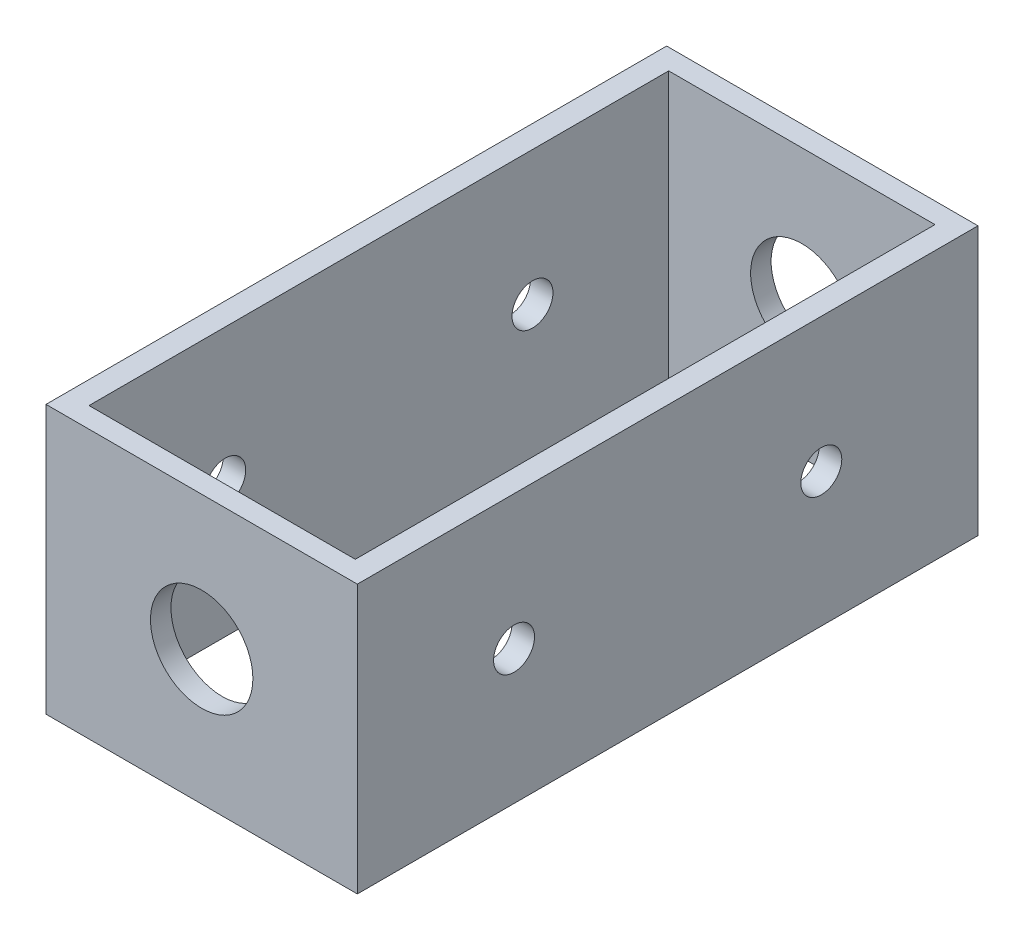
SolidWorks part; units mm, degrees
ref_plane "Front Plane" through (0, 0, 0) normal (0, 0, 1) x (1, 0, 0)
ref_plane "Top Plane" through (0, 0, 0) normal (0, 1, 0) x (1, 0, 0)
ref_plane "Right Plane" through (0, 0, 0) normal (1, 0, 0) x (0, 0, -1)
sketch "Sketch1" plane through (0, 0, 0) normal (0, 1, 0) x (1, 0, 0)
  line L1 (-7.6, -15.15) -> (7.6, -15.15)
  line L2 (-7.6, -15.15) -> (-7.6, 15.15)
  line L3 (-7.6, 15.15) -> (7.6, 15.15)
  line L4 (7.6, -15.15) -> (7.6, 15.15)
  line L5 (-7.6, -15.15) -> (7.6, 15.15) construction
  line L6 (-7.6, 15.15) -> (7.6, -15.15) construction
  line L7 (-6.5, -14.15) -> (6.5, -14.15)
  line L8 (-6.5, -14.15) -> (-6.5, 14.15)
  line L9 (-6.5, 14.15) -> (6.5, 14.15)
  line L10 (6.5, -14.15) -> (6.5, 14.15)
  line L11 (-6.5, -14.15) -> (6.5, 14.15) construction
  line L12 (-6.5, 14.15) -> (6.5, -14.15) construction
  point P0 (0, 0)
  point P6 (0, 0)
  dimension "D1" = 30.3
  dimension "D2" = 15.2
  dimension "D3" = 28.3
  dimension "D4" = 13
extrude "Boss-Extrude1" add sketch "Sketch1" along normal blind 13.1
sketch "Sketch2" plane through (7.6, 0, 0) normal (1, 0, 0) x (0, 0, -1)
  line L0 (-15.15, 13.1) -> (-15.15, 0) construction
  line L1 (-15.15, 13.1) -> (15.15, 13.1) construction
  circle A0 centre (-7.5, 6.55) radius 1
  circle A1 centre (7.5, 6.55) radius 1
  point P4 (0, 0)
  dimension "D1" = 2
  dimension "D2" = 15
  dimension "D3" = 7.65
  dimension "D4" = 6.55
extrude "Cut-Extrude1" cut sketch "Sketch2" against normal through all
sketch "Sketch3" plane through (0, 0, 15.15) normal (0, 0, 1) x (1, 0, 0)
  line L0 (-7.6, 13.1) -> (7.6, 13.1) construction
  line L1 (7.6, 13.1) -> (7.6, 0) construction
  circle A0 centre (0, 6.55) radius 2.5
  dimension "D1" = 5
  dimension "D2" = 6.55
  dimension "D3" = 7.6
extrude "Cut-Extrude2" cut sketch "Sketch3" against normal through all
